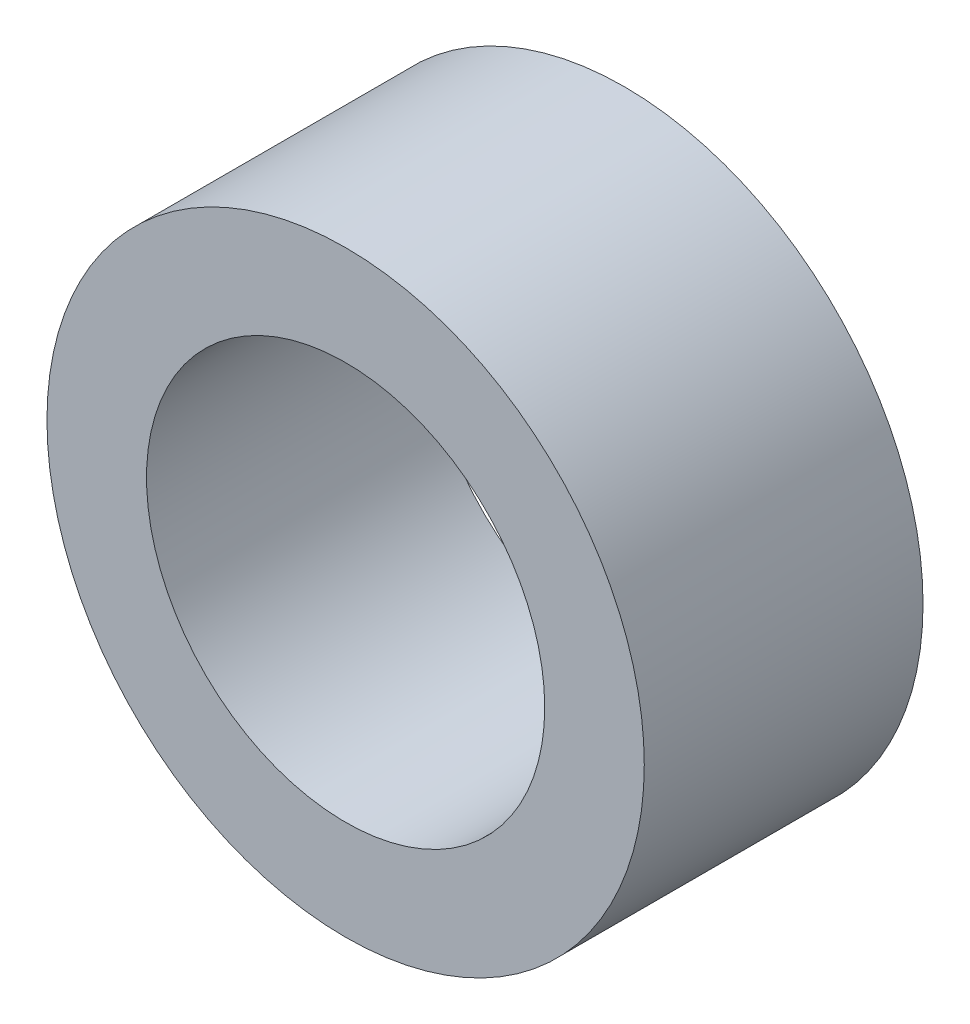
SolidWorks part; units mm, degrees
ref_plane "Front Plane" through (0, 0, 0) normal (0, 0, 1) x (1, 0, 0)
ref_plane "Top Plane" through (0, 0, 0) normal (0, 1, 0) x (1, 0, 0)
ref_plane "Right Plane" through (0, 0, 0) normal (1, 0, 0) x (0, 0, -1)
sketch "Sketch1" plane through (0, 0, 0) normal (0, 0, 1) x (1, 0, 0)
  circle A0 centre (0, 0) radius 30
  circle A1 centre (0, 0) radius 20
extrude "Boss-Extrude1" add sketch "Sketch1" along normal mid plane 28
